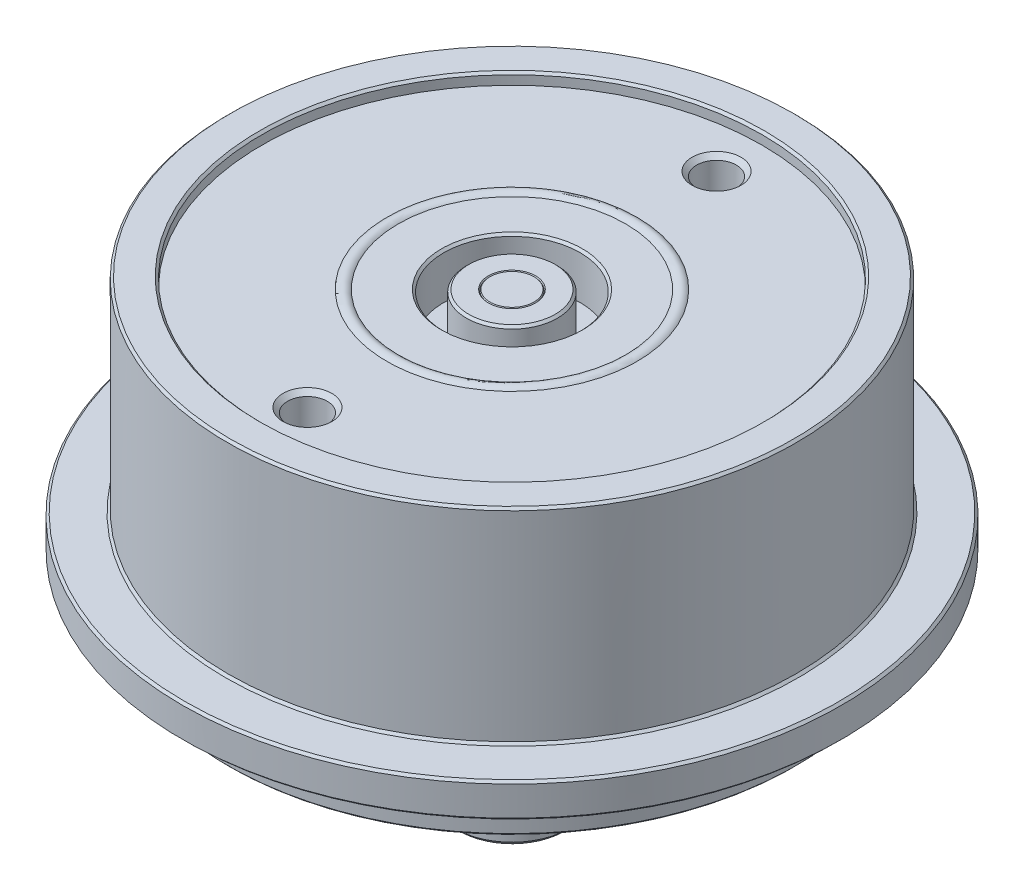
SolidWorks part; units mm, degrees
material "7079 Alloy"
ref_plane "Plane1" through (0, 0, 0) normal (0, 0, 1) x (1, 0, 0)
ref_plane "Plane2" through (0, 0, 0) normal (0, 1, 0) x (1, 0, 0)
ref_plane "Plane3" through (0, 0, 0) normal (1, 0, 0) x (0, 0, -1)
sketch "Sketch1" plane through (0, 0, 0) normal (0, 0, 1) x (1, 0, 0)
  line L0 (0, 0) -> (0, 34.8) construction
  line L1 (22, 24) -> (22, 25)
  line L2 (22, 25) -> (25, 25)
  line L3 (4, 24) -> (4, 20)
  line L4 (0, 24) -> (0, -15)
  line L5 (5, 0) -> (5, -15)
  line L6 (5, -15) -> (0, -15)
  line L7 (7.5118, 0.1212) -> (7.702, 0)
  line L8 (7.702, 0) -> (11.1902, 0)
  line L9 (25, 25) -> (25, 7)
  line L10 (25, 7) -> (29, 7)
  line L11 (29, 7) -> (29, 4)
  line L12 (29, 4) -> (25, 4)
  line L13 (25, 4) -> (25, 0)
  line L14 (25, 0) -> (15, 0)
  line L15 (5, 0) -> (5, 0.1)
  line L16 (5, 0.1) -> (5.1, 0)
  line L17 (5.1, 0) -> (7.2431, 0)
  line L18 (7.2431, 0) -> (7.3643, 0.1212)
  line L19 (7.3643, 0.1212) -> (7.5118, 0.1212)
  line L20 (12.3577, 0) -> (12.4592, 0.1)
  line L21 (11.1902, 0) -> (12.3577, 0)
  line L22 (14.874, 0) -> (15, 0.1)
  line L23 (12.4592, 0.1) -> (12.5741, 0.1)
  line L24 (12.5741, 0.1) -> (12.7218, 0)
  line L25 (4, 20) -> (6, 20)
  line L26 (2.0753, 24) -> (4, 24)
  line L27 (15, 0.1) -> (15, 0)
  line L28 (6, 24) -> (6, 20)
  line L29 (0, 24) -> (1.9345, 24)
  line L30 (6, 24) -> (10, 24)
  line L31 (1.9345, 24) -> (2, 23.9185)
  line L32 (2, 23.9185) -> (2.0753, 24)
  line L36 (11, 24) -> (22, 24)
  line L37 (12.7218, 0) -> (14.874, 0)
  arc A0 (10, 24) -> (11, 24) centre (10.5, 23.5) cw
  dimension "D2" = 25
  dimension "D3" = 4
  dimension "D4" = 22
  dimension "D5" = 1
  dimension "D6" = 3
  dimension "D7" = 25
  dimension "D8" = 15
  dimension "D9" = 5
  dimension "D10" = 29
  dimension "D11" = 4
  dimension "D12" = 25
  dimension "D14" = 4
  dimension "D15" = 6
  dimension "D25" = 15
revolve "Base-Revolve" add sketch "Sketch1" angle 360 about L0
sketch "Sketch11" plane through (0, 0, 0) normal (0, -1, 0) x (1, 0, 0)
  circle A3 centre (-21, 0) radius 1.6
  circle A4 centre (10.5, 18.1865) radius 1.6
  circle A5 centre (10.5, -18.1865) radius 1.6
extrude "Cut-Extrude11" cut sketch "Sketch11" against normal blind 8
sketch "Sketch12" plane through (0, 8, 0) normal (0, -1, 0) x (1, 0, 0)
  circle A1 centre (10.5, -18.1865) radius 1.6
  circle A2 centre (10.5, -18.1865) radius 1.6
  circle A4 centre (-21, 0) radius 1.6
  circle A5 centre (-21, 0) radius 1.6
  circle A8 centre (10.5, 18.1865) radius 1.6
  circle A9 centre (10.5, 18.1865) radius 1.6
  dimension "D1" = 0
  dimension "D2" = 0
  dimension "D3" = 0
extrude "Cut-Extrude12" cut sketch "Sketch12" against normal blind 2 draft 60
chamfer "Chamfer5" distance 0.2 angle 45 9 edges at (0, 4, -29) (0, 7, -29) (0, 25, -22) (0, 24, -6) (0, 24, -4) (0, 25, -25) (0, 0, -25) (0, 4, -25) (0, 7, -25)
sketch "Sketch13" plane through (0, 24, 0) normal (0, 1, 0) x (-1, 0, 0)
  circle A0 centre (0, -18) radius 1.75
  circle A1 centre (0, 18) radius 1.75
  dimension "D3" = 3.5
  dimension "D4" = 3.5
  dimension "D1" = 18
  dimension "D2" = 18
extrude "Cut-Extrude13" cut sketch "Sketch13" against normal blind 8
sketch "Sketch14" plane through (0, 16, 0) normal (0, 1, 0) x (-1, 0, 0)
  circle A0 centre (0, -18) radius 1.75
  circle A1 centre (0, 18) radius 1.75
  dimension "D1" = 3.5
  dimension "D2" = 3.5
extrude "Cut-Extrude14" cut sketch "Sketch14" against normal blind 3 draft 55
chamfer "Chamfer4" distance 0.4 angle 45 6 edges at (0, 24, -16.25) (0, 24, 19.75) (0, -15, -5) (-21, 0, -1.6) (10.5, 0, 16.5865) (10.5, 0, -19.7865)
